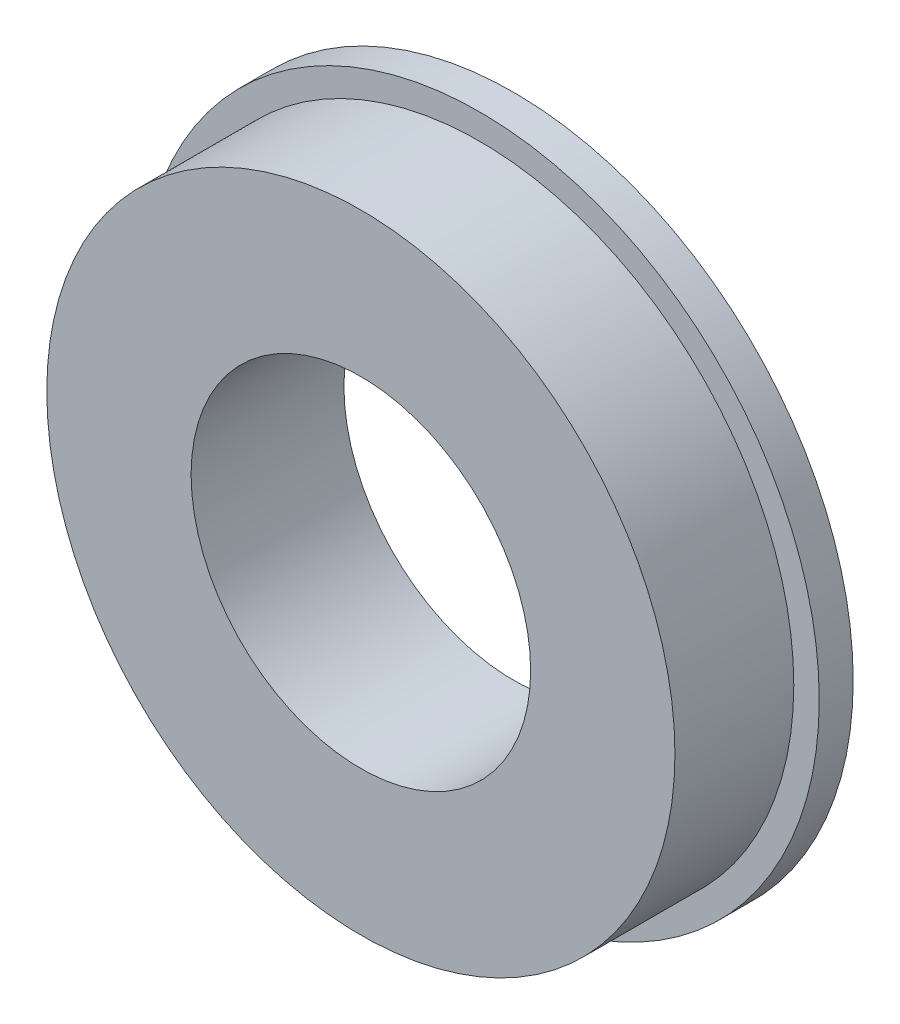
SolidWorks part; units mm, degrees
material "AISI 304"
ref_plane "前视基准面" through (0, 0, 0) normal (0, 0, 1) x (1, 0, 0)
ref_plane "上视基准面" through (0, 0, 0) normal (0, 1, 0) x (1, 0, 0)
ref_plane "右视基准面" through (0, 0, 0) normal (1, 0, 0) x (0, 0, -1)
sketch "草图1" plane through (0, 0, 0) normal (0, 0, 1) x (1, 0, 0)
  circle A0 centre (0, 0) radius 20
  dimension "D1" = 40
extrude "凸台-拉伸1" add sketch "草图1" along normal blind 2
sketch "草图2" plane through (0, 0, 2) normal (0, 0, 1) x (1, 0, 0)
  circle A0 centre (0, 0) radius 18.5
  dimension "D1" = 37
extrude "凸台-拉伸2" add sketch "草图2" along normal blind 7
sketch "草图3" plane through (0, 0, 9) normal (0, 0, 1) x (1, 0, 0)
  circle A0 centre (0, 0) radius 10
  dimension "D1" = 20
extrude "切除-拉伸1" cut sketch "草图3" against normal through all
sketch "草图4" plane through (0, 0, 0) normal (0, 0, -1) x (-1, 0, 0)
  circle A0 centre (0, 0) radius 16.6386
  circle A1 centre (0, 0) radius 14.1664
extrude "切除-拉伸2" cut sketch "草图4" against normal blind 0.5
